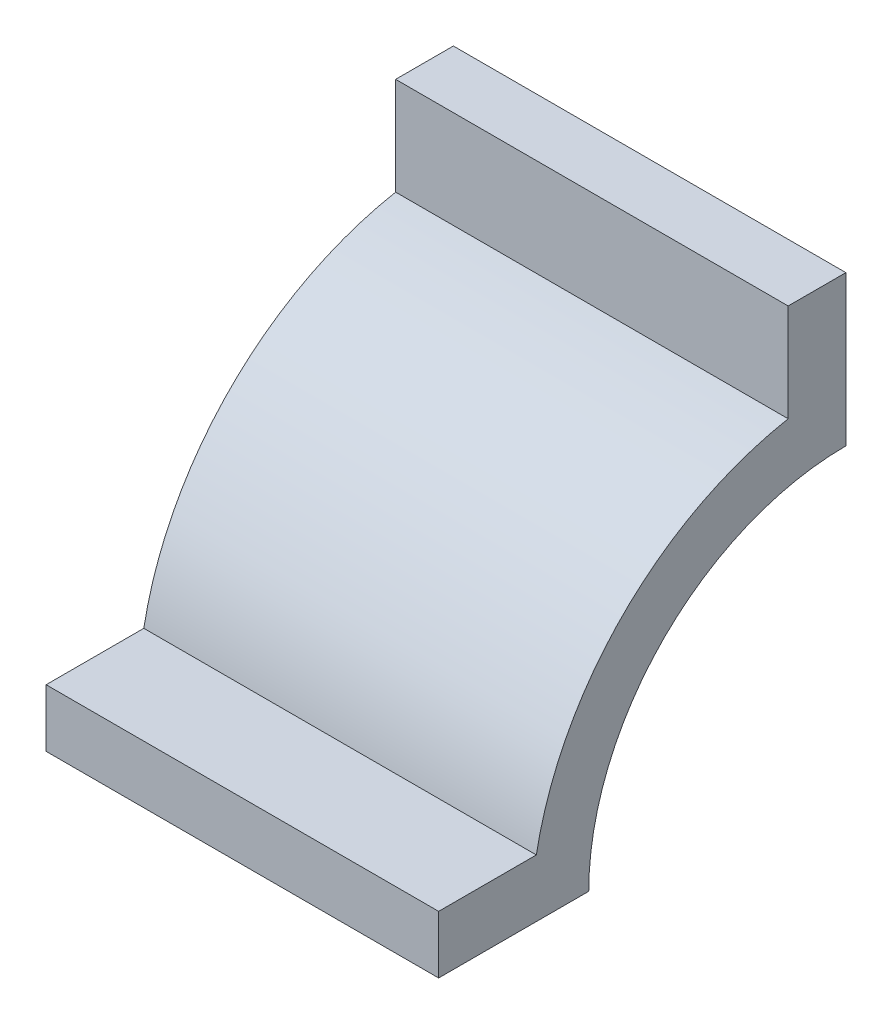
SolidWorks part; units mm, degrees
ref_plane "Front Plane" through (0, 0, 0) normal (0, 0, 1) x (1, 0, 0)
ref_plane "Top Plane" through (0, 0, 0) normal (0, 1, 0) x (1, 0, 0)
ref_plane "Right Plane" through (0, 0, 0) normal (1, 0, 0) x (0, 0, -1)
sketch "Sketch1" plane through (0, 0, 0) normal (1, 0, 0) x (0, 0, -1)
  line L0 (-35.275, 0) -> (-22.275, 0)
  line L2 (-26.8128, 5) -> (-35.275, 5)
  line L3 (-35.275, 5) -> (-35.275, 0)
  line L5 (0, 22.275) -> (0, 35.275)
  line L6 (0, 35.275) -> (-5, 35.275)
  line L7 (-5, 35.275) -> (-5, 26.8128)
  arc A0 (-22.275, 0) -> (0, 22.275) centre (0, 0) cw
  arc A1 (-5, 26.8128) -> (-26.8128, 5) centre (0, 0) ccw
  point P3 (0, 0)
  point P4 (-16.2941, 4.4314)
  point P9 (12.1498, 19.3481)
  point P13 (7.2284, 24.2566)
  point P14 (0, 0)
  point P15 (1.2887, 1.946)
  point P16 (0.4075, 0)
  dimension "D1" = 22.275
  dimension "D4" = 5
  dimension "D2" = 5
  dimension "D3" = 5
  dimension "D5" = 13
  dimension "D6" = 13
extrude "Boss-Extrude1" add sketch "Sketch1" along normal blind 34 contours L5 L6 L7 A1 L2 L3 L0 A0
